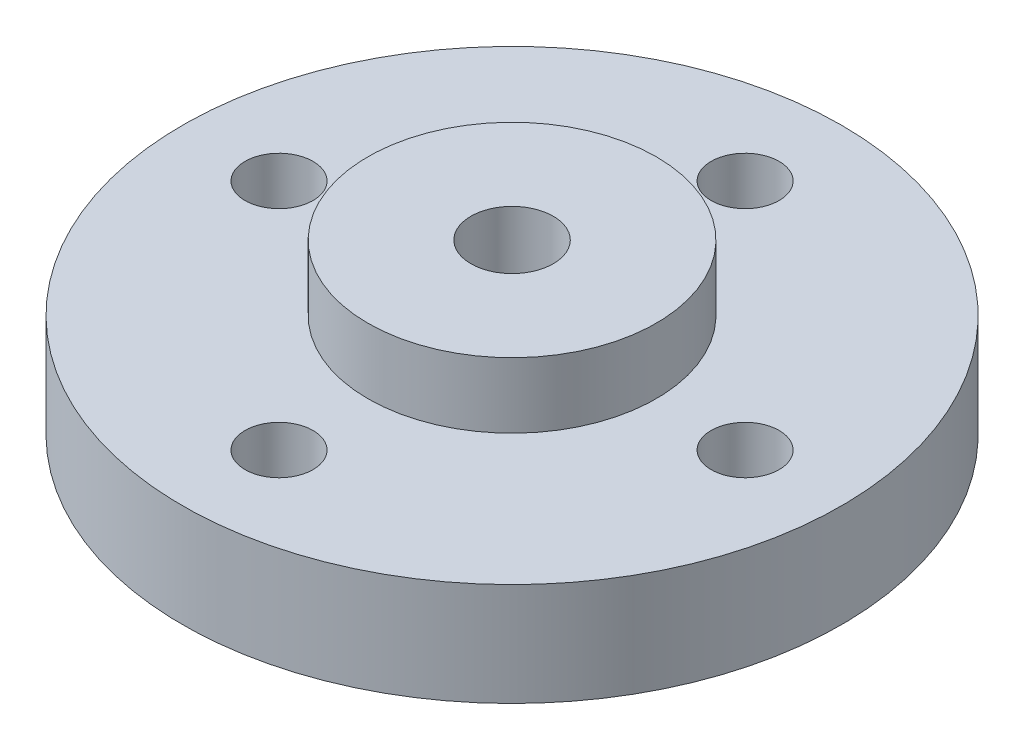
SolidWorks part; units mm, degrees
ref_plane "Front" through (0, 0, 0) normal (0, 0, 1) x (1, 0, 0)
ref_plane "Top" through (0, 0, 0) normal (0, 1, 0) x (1, 0, 0)
ref_plane "Right" through (0, 0, 0) normal (1, 0, 0) x (0, 0, -1)
sketch "Sketch1" plane through (0, 0, 0) normal (0, 1, 0) x (1, 0, 0)
  circle A0 centre (0, 0) radius 7
  circle A1 centre (0, 0) radius 2
extrude "Boss-Extrude1" add sketch "Sketch1" along normal blind 3.175
sketch "Sketch2" plane through (0, 0, 0) normal (0, -1, 0) x (-1, 0, 0)
  line L1 (3.9144, 0) -> (1.9572, 3.39)
  line L2 (1.9572, 3.39) -> (-1.9572, 3.39)
  line L3 (-1.9572, 3.39) -> (-3.9144, 0)
  line L4 (-3.9144, 0) -> (-1.9572, -3.39)
  line L5 (-1.9572, -3.39) -> (1.9572, -3.39)
  line L6 (1.9572, -3.39) -> (3.9144, 0)
  circle A0 centre (0, 0) radius 3.39 construction
  circle A1 centre (0, 0) radius 16
  circle A2 centre (0, 0) radius 11.3137
  circle A3 centre (11.3137, 0) radius 1.65
  circle A4 centre (0, 11.3137) radius 1.65
  circle A5 centre (-11.3137, 0) radius 1.65
  circle A6 centre (0, -11.3137) radius 1.65
  circle M1 centre (0, 0) radius 7
extrude "Boss-Extrude2" add sketch "Sketch2" along normal blind 5 separate body contours A1 A6 A2 A5 A4 A3 | A6 A2 A3 A4 A5 M1 | L6 L5 L4 L3 L2 L1 M1
